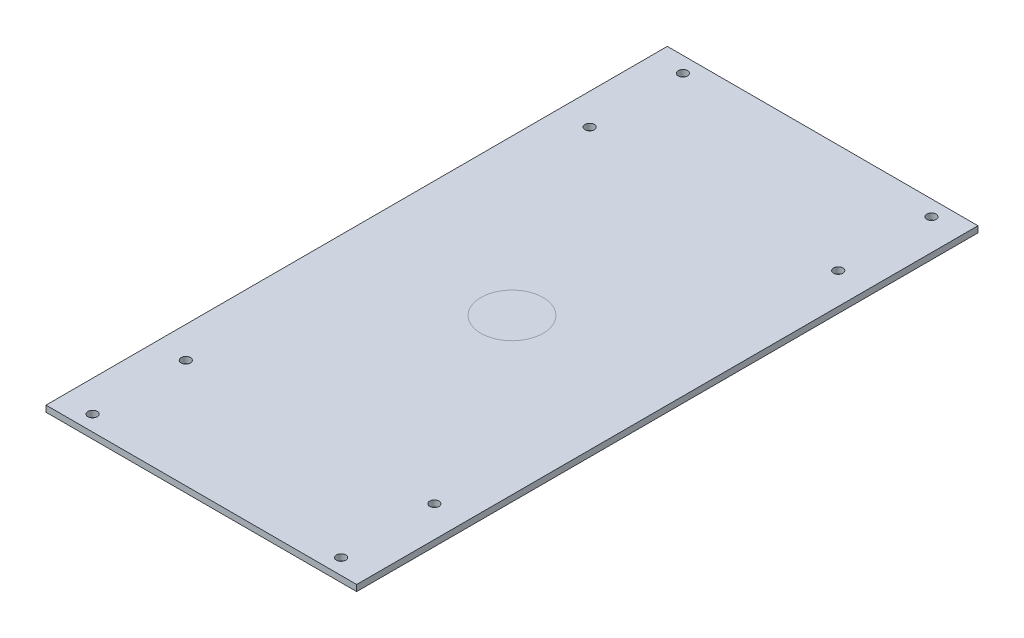
SolidWorks part; units mm, degrees
material "custom standard carbon fiber"
ref_plane "Front Plane" through (0, 0, 0) normal (0, 0, 1) x (1, 0, 0)
ref_plane "Top Plane" through (0, 0, 0) normal (0, 1, 0) x (1, 0, 0)
ref_plane "Right Plane" through (0, 0, 0) normal (1, 0, 0) x (0, 0, -1)
sketch "Sketch1" plane through (0, 0, 0) normal (0, 1, 0) x (1, 0, 0)
  line L1 (-50, 100) -> (50, 100)
  line L2 (-50, 100) -> (-50, -100)
  line L3 (-50, -100) -> (50, -100)
  line L4 (50, 100) -> (50, -100)
  line L5 (-50, 100) -> (50, -100) construction
  line L6 (-50, -100) -> (50, 100) construction
  point P0 (0, 0)
  dimension "D1" = 200
  dimension "D2" = 100
extrude "Boss-Extrude1" add sketch "Sketch1" along normal blind 2 contours L2 L3 L4 L1
sketch "Sketch2" plane through (0, 2, 0) normal (0, 1, 0) x (1, 0, 0)
  line L0 (50, 100) -> (50, -100) construction
  line L1 (-50, 100) -> (50, 100) construction
  line L2 (-50, 100) -> (-50, -100) construction
  line L3 (-50, -100) -> (50, -100) construction
  point P0 (-40, 95)
  point P1 (40, 95)
  point P2 (-40, -95)
  point P3 (40, -95)
  point P12 (-40, 65)
  point P13 (40, 65)
  point P14 (-40, -65)
  point P15 (40, -65)
  dimension "D1" = 10
  dimension "D2" = 5
  dimension "D3" = 5
  dimension "D4" = 10
  dimension "D5" = 5
  dimension "D6" = 10
  dimension "D7" = 5
  dimension "D8" = 10
  dimension "D9" = 30
  dimension "D10" = 30
  dimension "D11" = 30
  dimension "D12" = 30
hole_wizard "Ø3.0mm Dowel Hole1" positions "Sketch5" profile "Sketch6" hole size "Ø3.0" standard "ANSI Metric" end condition through all
sketch "Sketch5" plane through (0, 2, 0) normal (0, 1, 0) x (1, 0, 0)
  point P0 (-40, 95)
  point P3 (40, 95)
  point P6 (-40, 65)
  point P9 (40, 65)
  point P12 (-40, -65)
  point P15 (-40, -95)
  point P18 (40, -65)
  point P21 (40, -95)
sketch "Sketch6" plane through (-40, 2, -95) normal (1, 0, 0) x (0, 0, 1)
  line L0 (0, 0) -> (0, 2)
  line L1 (0, 2) -> (1.5, 2)
  line L2 (1.5, 2) -> (1.5, 0)
  line L5 (1.5, 0) -> (0, 0)
  line L11 (0, -6.35) -> (0, 107.95) construction
  dimension "Thru Hole Dia." = 3
  dimension "Thru Hole Depth" = 2
sketch "Sketch7" plane through (0, 2, 0) normal (0, 1, 0) x (1, 0, 0)
  circle A0 centre (0, 0) radius 10
  dimension "D1" = 20
split line "Split Line1"
